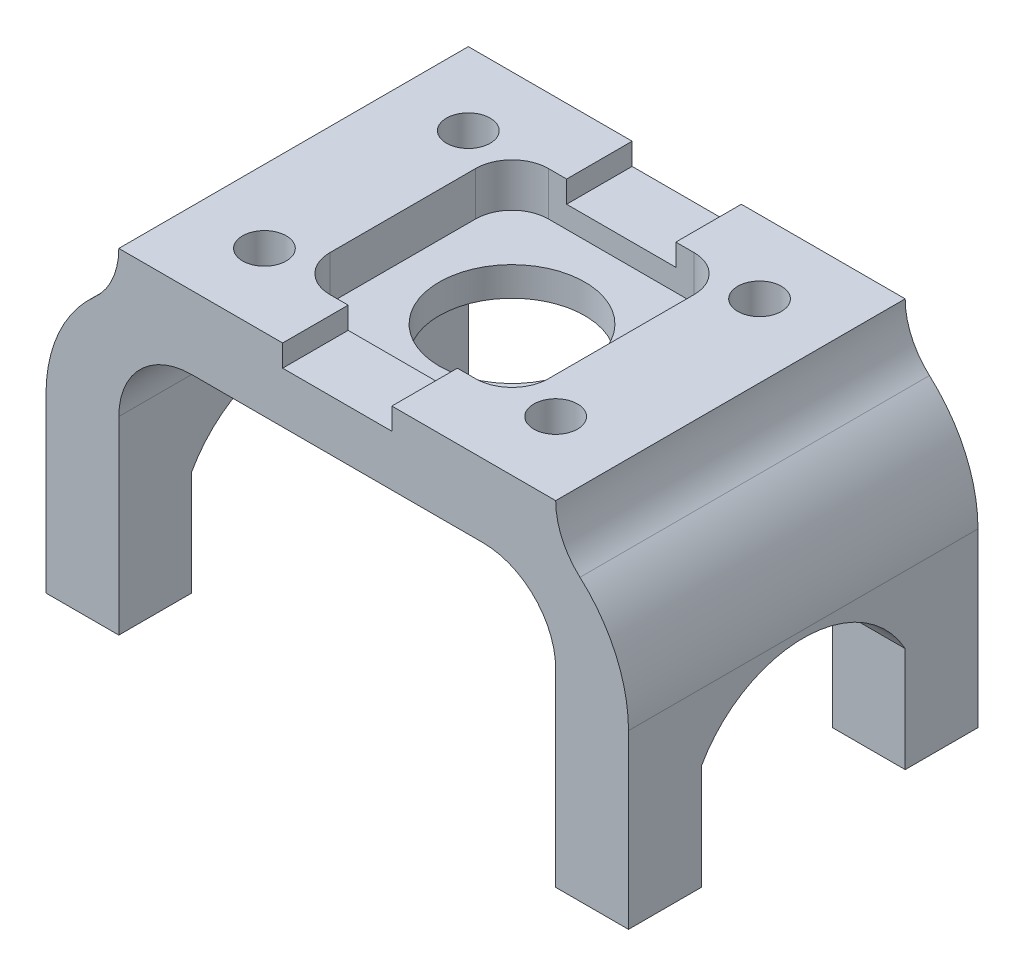
SolidWorks part; units mm, degrees
ref_plane "Alzado" through (0, 0, 0) normal (0, 0, 1) x (1, 0, 0)
ref_plane "Planta" through (0, 0, 0) normal (0, 1, 0) x (1, 0, 0)
ref_plane "Vista lateral" through (0, 0, 0) normal (1, 0, 0) x (0, 0, -1)
sketch "Croquis1" plane through (0, 0, 0) normal (0, 0, 1) x (1, 0, 0)
  line L0 (-3.5, 0) -> (-4, 0)
  line L1 (0, 0) -> (-0.5, 0)
  line L2 (0, 0) -> (0, 1.182)
  line L3 (-0.5, 2.3) -> (-1.625, 2.3)
  line L4 (-4, 0) -> (-4, 1.182)
  line L6 (-0.5, 0) -> (-0.5, 1.3)
  line L7 (-1, 1.8) -> (-3, 1.8)
  line L8 (-3.5, 0) -> (-3.5, 1.3)
  line L9 (-2, 1.8) -> (-2, 2.15) construction
  line L11 (-2.375, 2.3) -> (-2.375, 2.15)
  line L12 (-2.375, 2.15) -> (-1.625, 2.15)
  line L13 (-1.625, 2.3) -> (-1.625, 2.15)
  line L14 (-2.375, 2.3) -> (-3.5, 2.3)
  arc A0 (-0.5, 1.3) -> (-1, 1.8) centre (-1, 1.3) ccw
  arc A1 (-3, 1.8) -> (-3.5, 1.3) centre (-3, 1.3) ccw
  arc A2 (-3.5, 2.3) -> (-3.6667, 1.9273) centre (-4, 2.3) cw
  arc A3 (-3.6667, 1.9273) -> (-4, 1.182) centre (-3, 1.182) ccw
  arc A4 (-0.5, 2.3) -> (-0.3333, 1.9273) centre (0, 2.3) ccw
  arc A5 (-0.3333, 1.9273) -> (0, 1.182) centre (-1, 1.182) cw
  dimension "D4" = 0.5
  dimension "D8" = 0.5
  dimension "D9" = 1
  dimension "D1" = 4
  dimension "D2" = 3
  dimension "D3" = 0.5
  dimension "D5" = 1.3
  dimension "D6" = 0.15
  dimension "D7" = 0.75
  dimension "D10" = 3
extrude "Saliente-Extruir1" add sketch "Croquis1" along normal mid plane 2.4
sketch "Croquis2" plane through (0, 2.3, 0) normal (0, 1, 0) x (1, 0, 0)
  line L0 (-0.5, -1.2) -> (-0.5, 1.2) construction
  line L1 (-2.5, 0.75) -> (-1.5, 0.75)
  line L2 (-2.75, 0.5) -> (-2.75, -0.5)
  line L3 (-2.5, -0.75) -> (-1.5, -0.75)
  line L4 (-1.25, 0.5) -> (-1.25, -0.5)
  line L5 (-2.75, 0.75) -> (-1.25, -0.75) construction
  line L6 (-2.75, -0.75) -> (-1.25, 0.75) construction
  line L7 (-3.5, -1.2) -> (-3.5, 1.2) construction
  line L8 (-1.625, 1.2) -> (-2.375, 1.2) construction
  arc A0 (-2.75, -0.5) -> (-2.5, -0.75) centre (-2.5, -0.5) ccw
  arc A1 (-1.5, -0.75) -> (-1.25, -0.5) centre (-1.5, -0.5) ccw
  arc A2 (-1.5, 0.75) -> (-1.25, 0.5) centre (-1.5, 0.5) cw
  arc A3 (-2.5, 0.75) -> (-2.75, 0.5) centre (-2.5, 0.5) ccw
  point P0 (-2, 0)
  point P8 (-0.5, 0)
  dimension "D4" = 0.25
  dimension "D1" = 0.75
  dimension "D2" = 0.75
  dimension "D3" = 0.45
extrude "Cortar-Extruir1" cut sketch "Croquis2" against normal blind 0.3
sketch "Croquis3" plane through (0, 2, 0) normal (0, 1, 0) x (1, 0, 0)
  line L0 (-1.625, 1.2) -> (-2.375, 1.2) construction
  circle A0 centre (-2, 0) radius 0.5
  point P5 (-2, 1.2)
  dimension "D1" = 1
extrude "Cortar-Extruir2" cut sketch "Croquis3" against normal through all
sketch "Croquis4" plane through (0, 2.3, 0) normal (0, 1, 0) x (1, 0, 0)
  line L0 (-2, 0.75) -> (-2, 1.2) construction
  line L1 (-2.375, 0.75) -> (-1.625, 0.75) construction
  line L2 (-1.625, 1.2) -> (-2.375, 1.2) construction
  line L3 (0, 0) -> (-1.25, 0) construction
  line L4 (0, -1.2) -> (0, 1.2) construction
  line L5 (-1.25, -0.5) -> (-1.25, 0.5) construction
  circle A0 centre (-1, 0.7) radius 0.15
  circle A1 centre (-3, 0.7) radius 0.15
  circle A2 centre (-3, -0.7) radius 0.15
  circle A3 centre (-1, -0.7) radius 0.15
  dimension "D1" = 0.3
  dimension "D2" = 1.4
  dimension "D3" = 2
extrude "Cortar-Extruir3" cut sketch "Croquis4" against normal through all
sketch "Croquis5" plane through (0, 0, 0) normal (1, 0, 0) x (0, 0, -1)
  line L0 (-1.2, 0) -> (1.2, 0) construction
  line L1 (-0.7, 0) -> (0.7, 0)
  line L2 (-0.7, 0) -> (-0.7, 0.72)
  line L4 (0.7, 0) -> (0.7, 0.72)
  arc A0 (-0.7, 0.72) -> (0.7, 0.72) centre (0, 0.3327) cw
  dimension "D2" = 0.8
  dimension "D1" = 1.4
  dimension "D3" = 0.72
extrude "Cortar-Extruir4" cut sketch "Croquis5" against normal through all
